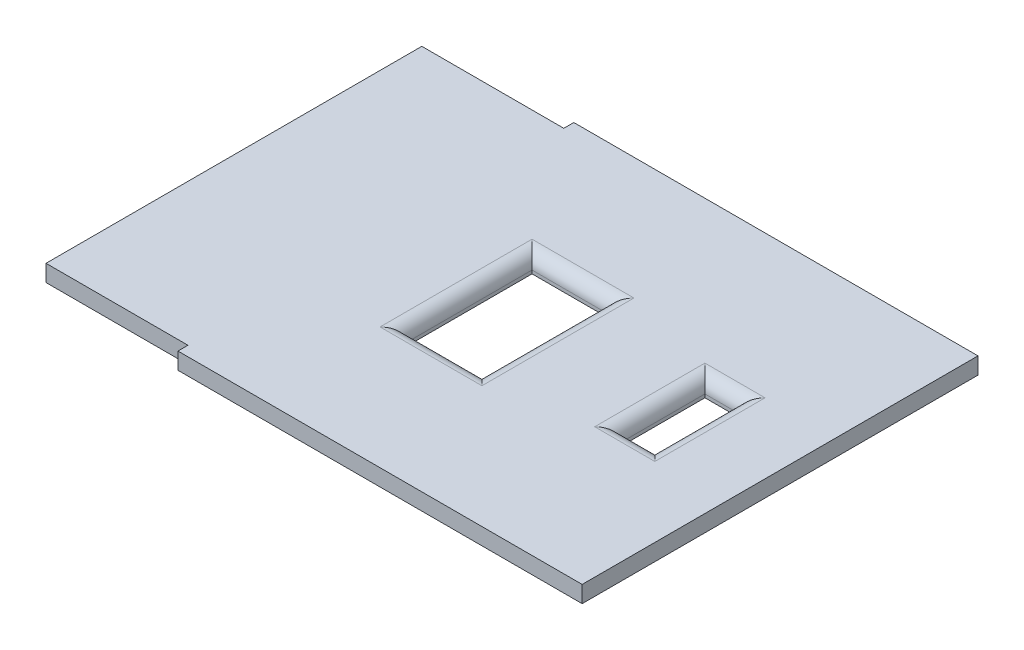
SolidWorks part; units mm, degrees
ref_plane "Front Plane" through (0, 0, 0) normal (0, 0, 1) x (1, 0, 0)
ref_plane "Top Plane" through (0, 0, 0) normal (0, 1, 0) x (1, 0, 0)
ref_plane "Right Plane" through (0, 0, 0) normal (1, 0, 0) x (0, 0, -1)
sketch "Sketch1" plane through (0, 0, 0) normal (0, 1, 0) x (1, 0, 0)
  line L0 (0, 28.575) -> (0, -28.575)
  line L1 (0, -28.575) -> (21.59, -28.575)
  line L2 (21.59, -28.575) -> (21.59, -30.099)
  line L3 (21.59, -30.099) -> (83.058, -30.099)
  line L4 (83.058, -30.099) -> (83.058, 30.099)
  line L5 (83.058, 30.099) -> (21.59, 30.099)
  line L6 (21.59, 30.099) -> (21.59, 28.575)
  line L7 (21.59, 28.575) -> (0, 28.575)
  point P8 (81.6305, 27.5903)
  point P10 (82.55, -29.0116)
  point P13 (0, 0)
  dimension "D1" = 60.198
  dimension "D2" = 83.058
  dimension "D3" = 57.15
  dimension "D4" = 21.59
extrude "Boss-Extrude1" add sketch "Sketch1" along normal blind 2.54
sketch "Sketch2" plane through (0, 2.54, 0) normal (0, 1, 0) x (1, 0, 0)
  line L0 (0, 0) -> (83.058, 0) construction
  line L1 (35.814, -9.525) -> (47.244, -9.525)
  line L2 (35.814, -9.525) -> (35.814, 9.525)
  line L3 (35.814, 9.525) -> (47.244, 9.525)
  line L4 (47.244, -9.525) -> (47.244, 9.525)
  line L5 (35.814, -9.525) -> (47.244, 9.525) construction
  line L6 (35.814, 9.525) -> (47.244, -9.525) construction
  line L7 (65.278, -6.35) -> (70.358, -6.35)
  line L8 (65.278, -6.35) -> (65.278, 6.35)
  line L9 (65.278, 6.35) -> (70.358, 6.35)
  line L10 (70.358, -6.35) -> (70.358, 6.35)
  line L11 (65.278, -6.35) -> (70.358, 6.35) construction
  line L12 (65.278, 6.35) -> (70.358, -6.35) construction
  line L13 (83.058, -30.099) -> (83.058, 30.099) construction
  point P0 (41.529, 0)
  point P5 (67.818, 0)
  point P15 (41.529, 0)
  point P16 (69.2352, 0)
  dimension "D1" = 19.05
  dimension "D2" = 11.43
  dimension "D3" = 5.08
  dimension "D4" = 12.7
  dimension "D5" = 12.7
extrude "Cut-Extrude1" cut sketch "Sketch2" against normal through all
fillet "Fillet1" radius 2.032 8 edges at (47.244, 2.54, 0) (41.529, 2.54, 9.525) (35.814, 2.54, 0) (41.529, 2.54, -9.525) (70.358, 2.54, 0) (67.818, 2.54, 6.35) (65.278, 2.54, 0) (67.818, 2.54, -6.35)
